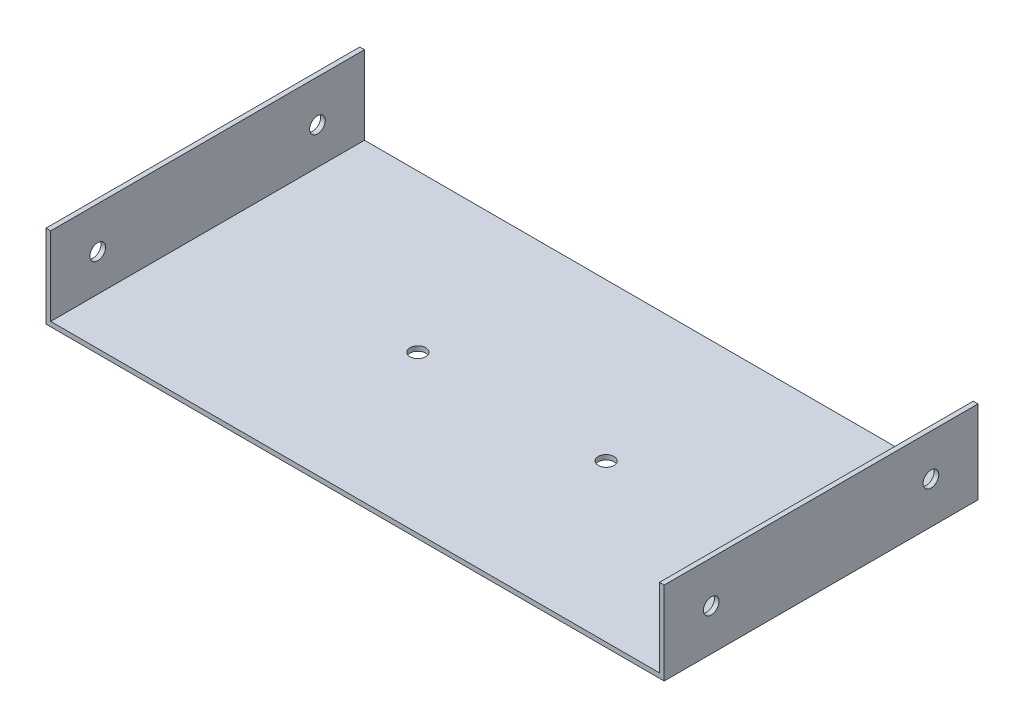
SolidWorks part; units mm, degrees
ref_plane "Front Plane" through (0, 0, 0) normal (0, 0, 1) x (1, 0, 0)
ref_plane "Top Plane" through (0, 0, 0) normal (0, 1, 0) x (1, 0, 0)
ref_plane "Right Plane" through (0, 0, 0) normal (1, 0, 0) x (0, 0, -1)
sketch "Sketch1" plane through (0, 0, 0) normal (0, 1, 0) x (1, 0, 0)
  line L1 (-197, 100) -> (197, 100)
  line L2 (-197, 100) -> (-197, -100)
  line L3 (-197, -100) -> (197, -100)
  line L4 (197, 100) -> (197, -100)
  line L5 (-197, 100) -> (197, -100) construction
  line L6 (-197, -100) -> (197, 100) construction
  point P1 (0, 0)
  dimension "D1" = 394
  dimension "200" = 200
extrude "Boss-Extrude1" add sketch "Sketch1" along normal blind 3
sketch "Sketch2" plane through (0, 3, 0) normal (0, 1, 0) x (1, 0, 0)
  line L6 (-197, 100) -> (-194, 100)
  line L7 (197, 100) -> (-197, 100) construction
  line L8 (-194, 100) -> (-194, -100)
  line L9 (-197, -100) -> (197, -100) construction
  line L10 (-194, -100) -> (-197, -100)
  line L11 (-197, -100) -> (-197, 100)
  line L12 (197, 100) -> (194, 100)
  line L13 (194, 100) -> (194, -100)
  line L14 (194, -100) -> (197, -100)
  line L15 (197, -100) -> (197, 100)
  dimension "D1" = 3
  dimension "D2" = 3
extrude "Boss-Extrude2" add sketch "Sketch2" along normal blind 50 contours L15 L12 L13 L14 | L11 L6 L8 L10
sketch "Sketch3" plane through (197, 0, 0) normal (1, 0, 0) x (0, 0, -1)
  line L0 (-100, 53) -> (100, 53) construction
  line L2 (100, 53) -> (100, 0) construction
  line L3 (-100, 53) -> (-100, 0) construction
  circle A0 centre (70, 26.5) radius 5
  circle A1 centre (-70, 26.5) radius 5
  dimension "D1" = 10
  dimension "D2" = 10
  dimension "D3" = 26.5
  dimension "D4" = 26.5
  dimension "D5" = 30
  dimension "D6" = 30
extrude "Cut-Extrude1" cut sketch "Sketch3" against normal through all
sketch "Sketch4" plane through (0, 0, 0) normal (0, -1, 0) x (1, 0, 0)
  line L0 (-197, -100) -> (-197, 100) construction
  line L1 (197, 100) -> (197, -100) construction
  line L2 (-197, 100) -> (197, 100) construction
  circle A0 centre (60, 0) radius 5
  circle A1 centre (-60, 0) radius 5
  dimension "D1" = 10
  dimension "D2" = 137
  dimension "D3" = 137
  dimension "D4" = 100
extrude "Cut-Extrude2" cut sketch "Sketch4" against normal through all
